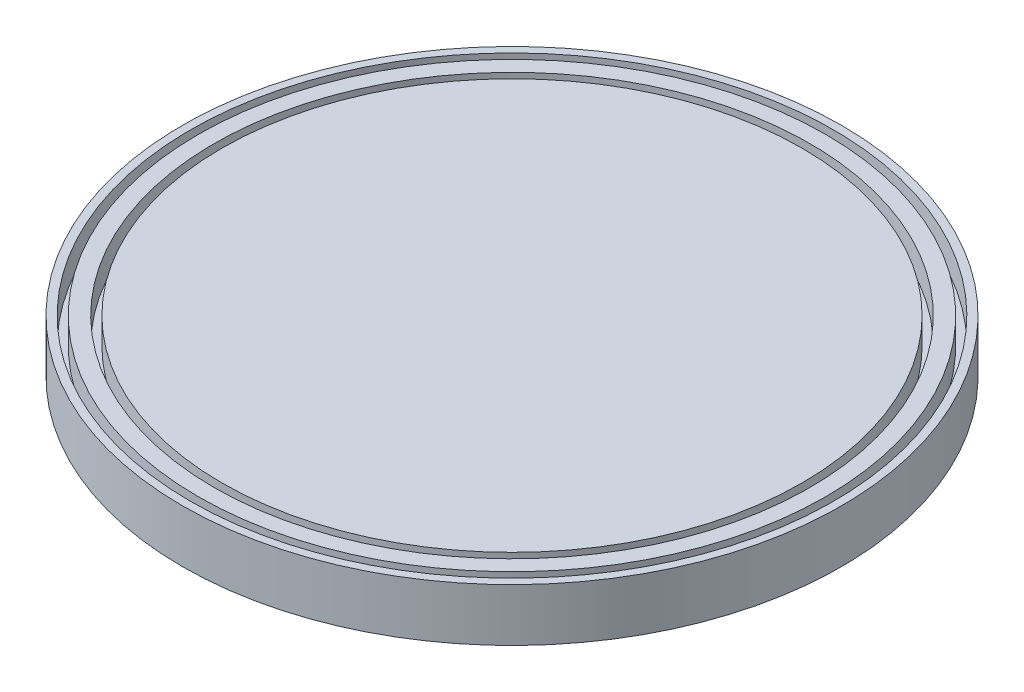
SolidWorks part; units mm, degrees
ref_plane "Front Plane" through (0, 0, 0) normal (0, 0, 1) x (1, 0, 0)
ref_plane "Top Plane" through (0, 0, 0) normal (0, 1, 0) x (1, 0, 0)
ref_plane "Right Plane" through (0, 0, 0) normal (1, 0, 0) x (0, 0, -1)
sketch "Sketch2" plane through (0, 0, 0) normal (0, 1, 0) x (1, 0, 0)
  circle A0 centre (0, 0) radius 62.5
extrude "Boss-Extrude1" add sketch "Sketch2" along normal blind 10
sketch "Sketch3" plane through (0, 10, 0) normal (0, 1, 0) x (1, 0, 0)
  circle A0 centre (0, 0) radius 55
  circle A1 centre (0, 0) radius 56.5
  circle A2 centre (0, 0) radius 59.5
  circle A3 centre (0, 0) radius 61
extrude "Cut-Extrude1" cut sketch "Sketch3" against normal blind 5 contours A1 A0 | A3 A2
